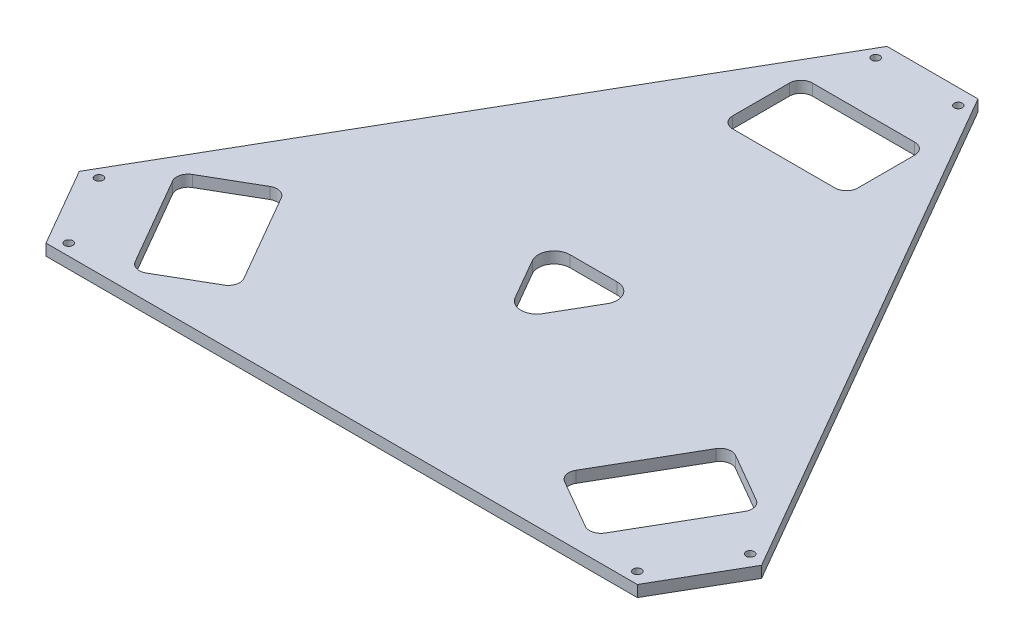
SolidWorks part; units mm, degrees
ref_plane "Plan de face" through (0, 0, 0) normal (0, 0, 1) x (1, 0, 0)
ref_plane "Plan de dessus" through (0, 0, 0) normal (0, 1, 0) x (1, 0, 0)
ref_plane "Plan de droite" through (0, 0, 0) normal (1, 0, 0) x (0, 0, -1)
sketch "Esquisse1" plane through (0, 0, 0) normal (0, 1, 0) x (1, 0, 0)
  line L0 (0, 10.9777) -> (0, -283.4709) construction
  line L1 (-32.5, -45.314) -> (-137.5, -227.1793)
  line L2 (-130, -283.4709) -> (130, -283.4709)
  line L3 (150, -248.8299) -> (20, -23.6633)
  line L4 (0, 10.9777) -> (0, -139.0223) construction
  line L5 (128.3244, -227.6552) -> (70.5135, -257.7866) construction
  line L7 (-32.5, -45.314) -> (-20, -23.6633)
  line L13 (100.8244, -275.2866) -> (98.0135, -210.1552) construction
  line L19 (-20, -23.6633) -> (20, -23.6633)
  line L21 (-137.5, -227.1793) -> (-150, -248.8299)
  line L24 (105, -283.4709) -> (-105, -283.4709)
  line L25 (32.5, -45.314) -> (137.5, -227.1793)
  line L26 (-32.5, -45.314) -> (0, 10.9777) construction
  line L27 (0, 10.9777) -> (32.5, -45.314) construction
  line L28 (137.5, -227.1793) -> (170, -283.4709) construction
  line L29 (170, -283.4709) -> (105, -283.4709) construction
  line L30 (-105, -283.4709) -> (-170, -283.4709) construction
  line L31 (-170, -283.4709) -> (-137.5, -227.1793) construction
  line L32 (-170, -283.4709) -> (-35.7661, -205.9709) construction
  line L33 (-103.3244, -270.9565) -> (-125.8244, -231.9854)
  line L34 (0, -283.4709) -> (0, -171.4176) construction
  line L35 (-96.4942, -272.7866) -> (-74.8436, -260.2866)
  line L36 (-123.9942, -225.1552) -> (-102.3436, -212.6552)
  line L37 (-73.0135, -253.4565) -> (-95.5135, -214.4854)
  line L38 (-100.8244, -275.2866) -> (-98.0135, -210.1552) construction
  line L39 (-128.3244, -227.6552) -> (-70.5135, -257.7866) construction
  line L40 (-22.5, -89.0223) -> (22.5, -89.0223)
  line L41 (-27.5, -84.0223) -> (-27.5, -59.0223)
  line L42 (27.5, -84.0223) -> (27.5, -59.0223)
  line L43 (-22.5, -54.0223) -> (22.5, -54.0223)
  line L44 (-27.5, -89.0223) -> (27.5, -54.0223) construction
  line L45 (27.5, -89.0223) -> (-27.5, -54.0223) construction
  line L46 (128.3244, -227.6552) -> (70.5135, -257.7866) construction
  line L47 (100.8244, -275.2866) -> (98.0135, -210.1552) construction
  line L48 (170, -283.4709) -> (35.7661, -205.9709) construction
  line L49 (73.0135, -253.4565) -> (95.5135, -214.4854)
  line L50 (123.9942, -225.1552) -> (102.3436, -212.6552)
  line L51 (96.4942, -272.7866) -> (74.8436, -260.2866)
  line L52 (103.3244, -270.9565) -> (125.8244, -231.9854)
  line L53 (128.3244, -227.6552) -> (70.5135, -257.7866) construction
  line L54 (100.8244, -275.2866) -> (98.0135, -210.1552) construction
  line L55 (170, -283.4709) -> (35.7661, -205.9709) construction
  line L56 (170, -283.4709) -> (137.5, -227.1793) construction
  line L57 (105, -283.4709) -> (170, -283.4709) construction
  line L61 (73.0135, -253.4565) -> (95.5135, -214.4854)
  line L62 (123.9942, -225.1552) -> (102.3436, -212.6552)
  line L63 (96.4942, -272.7866) -> (74.8436, -260.2866)
  line L64 (103.3244, -270.9565) -> (125.8244, -231.9854)
  line L67 (-130, -283.4709) -> (-150, -248.8299)
  line L69 (170, -283.4709) -> (35.7661, -205.9709) construction
  line L70 (170, -283.4709) -> (137.5, -227.1793) construction
  line L71 (105, -283.4709) -> (170, -283.4709) construction
  line L72 (130, -283.4709) -> (150, -248.8299)
  line L73 (73.0135, -253.4565) -> (95.5135, -214.4854)
  line L74 (123.9942, -225.1552) -> (102.3436, -212.6552)
  line L75 (96.4942, -272.7866) -> (74.8436, -260.2866)
  line L76 (103.3244, -270.9565) -> (125.8244, -231.9854)
  line L77 (105, -283.4709) -> (130, -283.4709)
  line L79 (32.5, -45.314) -> (137.5, -227.1793)
  arc A0 (123.9942, -225.1552) -> (125.8244, -231.9854) centre (121.4942, -229.4854) cw
  arc A1 (95.5135, -214.4854) -> (102.3436, -212.6552) centre (99.8436, -216.9854) cw
  arc A3 (22.5, -89.0223) -> (27.5, -84.0223) centre (22.5, -84.0223) ccw
  arc A4 (27.5, -59.0223) -> (22.5, -54.0223) centre (22.5, -59.0223) ccw
  arc A5 (-27.5, -59.0223) -> (-22.5, -54.0223) centre (-22.5, -59.0223) cw
  arc A6 (-27.5, -84.0223) -> (-22.5, -89.0223) centre (-22.5, -84.0223) ccw
  arc A7 (-74.8436, -260.2866) -> (-73.0135, -253.4565) centre (-77.3436, -255.9565) ccw
  arc A8 (-96.4942, -272.7866) -> (-103.3244, -270.9565) centre (-98.9942, -268.4565) cw
  arc A9 (-95.5135, -214.4854) -> (-102.3436, -212.6552) centre (-99.8436, -216.9854) ccw
  arc A10 (-123.9942, -225.1552) -> (-125.8244, -231.9854) centre (-121.4942, -229.4854) ccw
  arc A11 (123.9942, -225.1552) -> (125.8244, -231.9854) centre (121.4942, -229.4854) cw
  arc A12 (95.5135, -214.4854) -> (102.3436, -212.6552) centre (99.8436, -216.9854) cw
  arc A13 (96.4942, -272.7866) -> (103.3244, -270.9565) centre (98.9942, -268.4565) ccw
  arc A14 (74.8436, -260.2866) -> (73.0135, -253.4565) centre (77.3436, -255.9565) cw
  arc A18 (123.9942, -225.1552) -> (125.8244, -231.9854) centre (121.4942, -229.4854) cw
  arc A19 (95.5135, -214.4854) -> (102.3436, -212.6552) centre (99.8436, -216.9854) cw
  arc A20 (96.4942, -272.7866) -> (103.3244, -270.9565) centre (98.9942, -268.4565) ccw
  arc A21 (74.8436, -260.2866) -> (73.0135, -253.4565) centre (77.3436, -255.9565) cw
  arc A23 (96.4942, -272.7866) -> (103.3244, -270.9565) centre (98.9942, -268.4565) ccw
  arc A24 (74.8436, -260.2866) -> (73.0135, -253.4565) centre (77.3436, -255.9565) cw
  point P9 (0, 0)
  point P10 (0, 0)
  point P19 (0, -23.6633)
  point P32 (-99.4189, -242.7209)
  point P33 (0, -71.5223)
  point P88 (99.4189, -242.7209)
  dimension "D20" = 5
  dimension "D1" = 60
  dimension "D2" = 340
  dimension "D3" = 30
  dimension "D4" = 150
  dimension "D5" = 25
  dimension "D6" = 25
  dimension "D8" = 260
  dimension "D9" = 155
  dimension "D14" = 56
  dimension "D15" = 35
  dimension "D16" = 50
  dimension "D17" = 35
  dimension "D18" = 55
  dimension "D19" = 55
extrude "Boss.-Extru.1" add sketch "Esquisse1" along normal blind 5
sketch "Esquisse2" plane through (0, 5, 0) normal (0, 1, 0) x (1, 0, 0)
  line L0 (-150, -248.8299) -> (-145, -240.1697)
  line L4 (-130, -283.4709) -> (-120, -283.4709)
  line L6 (-130, -283.4709) -> (-130, -273.4709)
  line L7 (-150, -248.8299) -> (-141.3397, -253.8299)
  line L8 (0, -251.1744) -> (0, -89.0223) construction
  line L9 (-22.5, -89.0223) -> (22.5, -89.0223) construction
  line L14 (-120, -283.4709) -> (-120, -273.4709)
  line L23 (-145, -240.1697) -> (-136.3397, -245.1697)
  line L24 (-141.3397, -253.8299) -> (-136.3397, -245.1697)
  line L27 (-20, -23.6633) -> (-150, -248.8299) construction
  line L37 (-130, -273.4709) -> (-120, -273.4709)
  line L38 (-140, -266.1504) -> (-114.5744, -251.4709) construction
  line L50 (-130, -283.4709) -> (-150, -248.8299) construction
  line L78 (-130, -283.4709) -> (130, -283.4709) construction
  line L85 (-103.3244, -270.9565) -> (-125.8244, -231.9854) construction
  line L86 (-140.6699, -242.6697) -> (-145.6699, -251.3299) construction
  line L87 (-147.5, -244.4998) -> (-143.1699, -246.9998) construction
  line L88 (-130, -278.4709) -> (-120, -278.4709) construction
  line L89 (-125, -273.4709) -> (-125, -278.4709) construction
  line L94 (-20, -23.6633) -> (-25, -32.3236)
  line L95 (-20, -23.6633) -> (-11.3397, -28.6633)
  line L108 (-25, -32.3236) -> (-16.3397, -37.3236)
  line L109 (-11.3397, -28.6633) -> (-16.3397, -37.3236)
  line L110 (-150, -248.8299) -> (-20, -23.6633) construction
  line L111 (-15.6699, -26.1633) -> (-20.6699, -34.8236) construction
  line L112 (-22.5, -27.9935) -> (-18.1699, -30.4935) construction
  line L113 (0, -23.6633) -> (0, -54.0223) construction
  line L114 (-20, -23.6633) -> (20, -23.6633) construction
  line L115 (-22.5, -54.0223) -> (22.5, -54.0223) construction
  line L116 (22.5, -27.9935) -> (18.1699, -30.4935) construction
  line L117 (15.6699, -26.1633) -> (20.6699, -34.8236) construction
  line L118 (130, -283.4709) -> (120, -283.4709)
  line L119 (130, -283.4709) -> (130, -273.4709)
  line L120 (147.5, -244.4998) -> (143.1699, -246.9998) construction
  line L121 (140.6699, -242.6697) -> (145.6699, -251.3299) construction
  line L122 (140, -266.1504) -> (114.5744, -251.4709) construction
  line L123 (11.3397, -28.6633) -> (16.3397, -37.3236)
  line L124 (25, -32.3236) -> (16.3397, -37.3236)
  line L125 (20, -23.6633) -> (11.3397, -28.6633)
  line L126 (20, -23.6633) -> (25, -32.3236)
  line L131 (141.3397, -253.8299) -> (136.3397, -245.1697)
  line L132 (145, -240.1697) -> (136.3397, -245.1697)
  line L133 (150, -248.8299) -> (141.3397, -253.8299)
  line L134 (150, -248.8299) -> (145, -240.1697)
  line L135 (120, -283.4709) -> (120, -273.4709)
  line L136 (130, -273.4709) -> (120, -273.4709)
  line L137 (120, -278.4709) -> (130, -278.4709) construction
  line L138 (125, -273.4709) -> (125, -278.4709) construction
  dimension "D1" = 10
  dimension "D2" = 10
  dimension "D3" = 10
  dimension "D4" = 10
  dimension "D5" = 10
  dimension "D6" = 10
hole_wizard "Dégagement M31" positions "Esquisse3D1" profile "Esquisse4" hole size "M3" standard "BSI" end condition through all
sketch3d "Esquisse3D1"
  point P73 (-143.1699, 5, 246.9998)
  point P76 (-125, 5, 278.4709)
  point P79 (125, 5, 278.4709)
  point P82 (143.1699, 5, 246.9998)
  point P85 (-18.1699, 5, 30.4935)
  point P88 (18.1699, 5, 30.4935)
  point P91 (0, 0, 0)
  point P93 (0, 0, 0)
  point P95 (0, 0, 0)
sketch "Esquisse4" plane through (-143.1699, 5, 246.9998) normal (1, 0, 0) x (0, 0, 1)
  line L0 (0, 0) -> (0, 5)
  line L1 (0, 5) -> (1.8, 5)
  line L2 (1.8, 5) -> (1.8, 0)
  line L5 (1.8, 0) -> (0, 0)
  line L11 (0, -6.35) -> (0, 107.95) construction
  dimension "Diamètre du perçage jusqu'au prochain" = 3.6
  dimension "Profondeur du perçage jusqu'au prochain" = 5
sketch "Esquisse6" plane through (0, 0, 0) normal (0, -1, 0) x (-1, 0, 0)
  line L0 (0, -23.6633) -> (0, -283.4709) construction
  line L6 (-140, -266.1504) -> (35.6381, -164.7457) construction
  line L7 (-16.4378, -183.1729) -> (-6.0622, -201.1441)
  line L9 (-130, -283.4709) -> (130, -283.4709) construction
  line L10 (6.0622, -201.1441) -> (16.4378, -183.1729)
  line L11 (10.3756, -172.6729) -> (-10.3756, -172.6729)
  line L12 (140, -266.1504) -> (0, -185.3214) construction
  line L13 (130, -283.4709) -> (150, -248.8299) construction
  line L14 (-130, -283.4709) -> (-150, -248.8299) construction
  line L15 (-73.0135, -253.4565) -> (-95.5135, -214.4854) construction
  circle A0 centre (0, -185.6633) radius 12.9904 construction
  arc A1 (-6.0622, -201.1441) -> (6.0622, -201.1441) centre (0, -197.6441) ccw
  arc A2 (16.4378, -183.1729) -> (10.3756, -172.6729) centre (10.3756, -179.6729) ccw
  arc A3 (-16.4378, -183.1729) -> (-10.3756, -172.6729) centre (-10.3756, -179.6729) cw
  point P13 (0, -211.6441)
  point P16 (22.5, -172.6729)
  point P19 (-22.5, -172.6729)
  dimension "D2" = 162
  dimension "D3" = 7
  dimension "D1" = 45
  dimension "D4" = 90
extrude "Enlèv. mat.-Extru.2" cut sketch "Esquisse6" against normal blind 10
